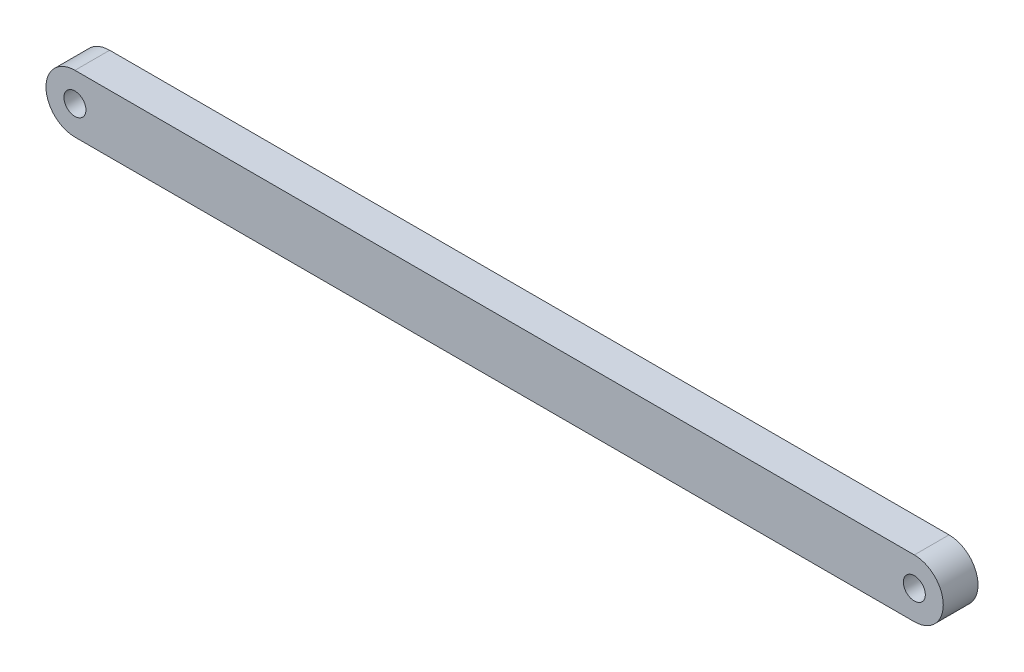
SolidWorks part; units mm, degrees
material "MDF"
ref_plane "Front Plane" through (0, 0, 0) normal (0, 0, 1) x (1, 0, 0)
ref_plane "Top Plane" through (0, 0, 0) normal (0, 1, 0) x (1, 0, 0)
ref_plane "Right Plane" through (0, 0, 0) normal (1, 0, 0) x (0, 0, -1)
sketch "Sketch1" plane through (0, 0, 0) normal (0, 0, 1) x (1, 0, 0)
  line L0 (0, -5) -> (0, 5) construction
  line L1 (-72.5, 5) -> (72.5, 5)
  line L2 (-72.5, -5) -> (72.5, -5)
  line L3 (72.5, 0) -> (-72.5, 0) construction
  arc A0 (72.5, 5) -> (72.5, -5) centre (72.5, 0) cw
  arc A1 (-72.5, 5) -> (-72.5, -5) centre (-72.5, 0) ccw
  circle A2 centre (-72.5, 0) radius 1.9
  circle A3 centre (72.5, 0) radius 1.9
  point P4 (0, 0)
  point P8 (0, 5)
  point P11 (0, -5)
  point P13 (0, 0)
  dimension "D3" = 3.8
  dimension "D4" = 3.8
  dimension "D1" = 10
  dimension "D2" = 145
extrude "Boss-Extrude1" add sketch "Sketch1" along normal blind 6
sketch "Sketch2" plane through (0, 0, 6) normal (0, 0, 1) x (1, 0, 0)
  line L0 (36.25, 0) -> (-36.25, 0) construction
  line L1 (-72.5, 1.9) -> (-72.5, -1.9) construction
  line L2 (-67.5, -2.5) -> (-5, -2.5)
  line L3 (-67.5, -2.5) -> (-67.5, 2.5)
  line L4 (-67.5, 2.5) -> (-5, 2.5)
  line L5 (-5, -2.5) -> (-5, 2.5)
  line L6 (-67.5, -2.5) -> (-5, 2.5) construction
  line L7 (-67.5, 2.5) -> (-5, -2.5) construction
  line L8 (5, -2.5) -> (67.5, -2.5)
  line L9 (5, -2.5) -> (5, 2.5)
  line L10 (5, 2.5) -> (67.5, 2.5)
  line L11 (67.5, -2.5) -> (67.5, 2.5)
  line L12 (5, -2.5) -> (67.5, 2.5) construction
  line L13 (5, 2.5) -> (67.5, -2.5) construction
  line L14 (72.5, 1.9) -> (72.5, -1.9) construction
  circle A0 centre (-72.5, 0) radius 1.9 construction
  circle A1 centre (72.5, 0) radius 1.9 construction
  point P4 (0, 0)
  dimension "D1" = 5
  dimension "D2" = 5
  dimension "D3" = 10
  dimension "D4" = 5
  dimension "D5" = 5
extrude "Cut-Extrude1" [suppressed] cut sketch "Sketch2" against normal through all
